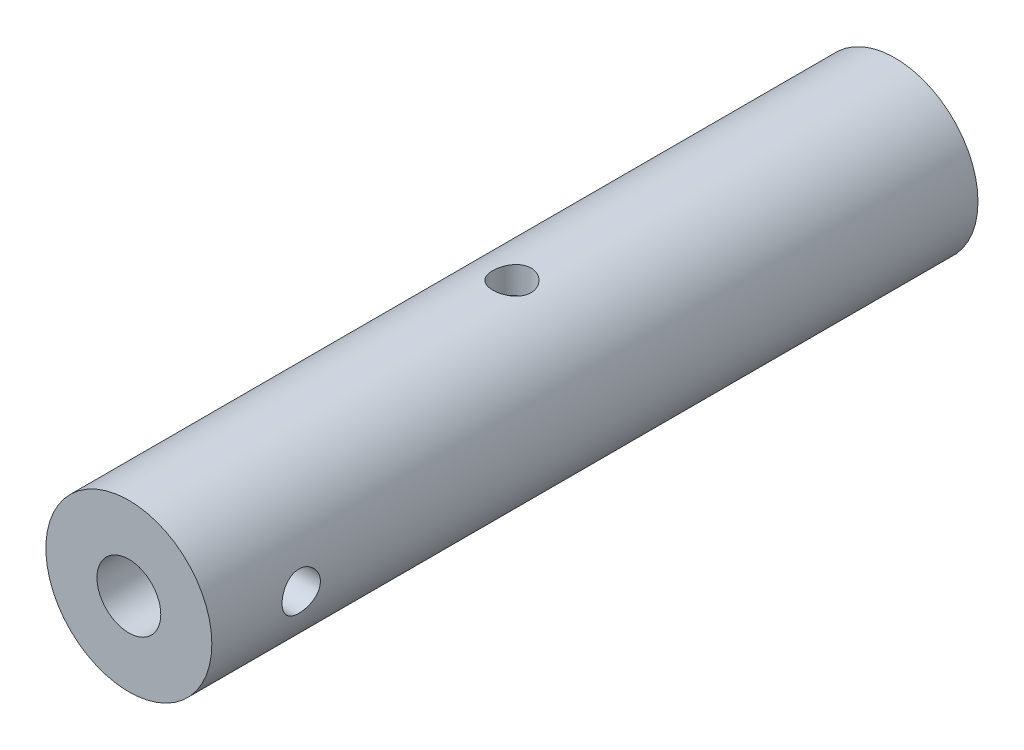
SolidWorks part; units mm, degrees
ref_plane "Alzado" through (0, 0, 0) normal (0, 0, 1) x (1, 0, 0)
ref_plane "Planta" through (0, 0, 0) normal (0, 1, 0) x (1, 0, 0)
ref_plane "Vista lateral" through (0, 0, 0) normal (1, 0, 0) x (0, 0, -1)
sketch "Croquis1" plane through (0, 0, 0) normal (0, 0, 1) x (1, 0, 0)
  circle A0 centre (0, 0) radius 6.5
  dimension "D1" = 13
extrude "Saliente-Extruir1" add sketch "Croquis1" along normal blind 45
sketch "Croquis2" plane through (0, 0, 0) normal (0, 0, -1) x (-1, 0, 0)
  circle A0 centre (0, 0) radius 5
  dimension "D1" = 10
extrude "Cortar-Extruir1" cut sketch "Croquis2" against normal blind 15
sketch "Croquis3" plane through (0, 0, 45) normal (0, 0, 1) x (1, 0, 0)
  line L1 (-5, 0) -> (-2.5, -4.3301)
  line L2 (-2.5, -4.3301) -> (2.5, -4.3301)
  line L3 (2.5, -4.3301) -> (5, 0)
  line L4 (5, 0) -> (2.5, 4.3301)
  line L5 (2.5, 4.3301) -> (-2.5, 4.3301)
  line L6 (-2.5, 4.3301) -> (-5, 0)
  circle A0 centre (0, 0) radius 5 construction
  dimension "D1" = 10
extrude "Cortar-Extruir2" cut sketch "Croquis3" against normal up to next
sketch "Croquis4" plane through (0, 0, 45) normal (0, 0, 1) x (1, 0, 0)
  circle A0 centre (0, 0) radius 6.5
extrude "Saliente-Extruir2" add sketch "Croquis4" along normal blind 15
sketch "Croquis5" plane through (0, 0, 60) normal (0, 0, 1) x (1, 0, 0)
  circle A0 centre (0, 0) radius 2.5
  dimension "D1" = 5
extrude "Cortar-Extruir3" cut sketch "Croquis5" against normal up to next
sketch "Croquis7" plane through (0, 0, 0) normal (1, 0, 0) x (0, 0, -1)
  line L0 (-60, 6.5) -> (-60, -6.5) construction
  circle A1 centre (-53, 0) radius 1.5
  dimension "D3" = 3
  dimension "D1" = 7
extrude "Cortar-Extruir4" cut sketch "Croquis7" against normal through all both and the other way through all
sketch "Croquis8" plane through (0, 0, 0) normal (0, 1, 0) x (1, 0, 0)
  line L0 (5, 0) -> (-5, 0) construction
  circle A0 centre (0, -30) radius 1.5
  dimension "D1" = 3
  dimension "D2" = 30
extrude "Cortar-Extruir5" cut sketch "Croquis8" against normal through all both and the other way through all
